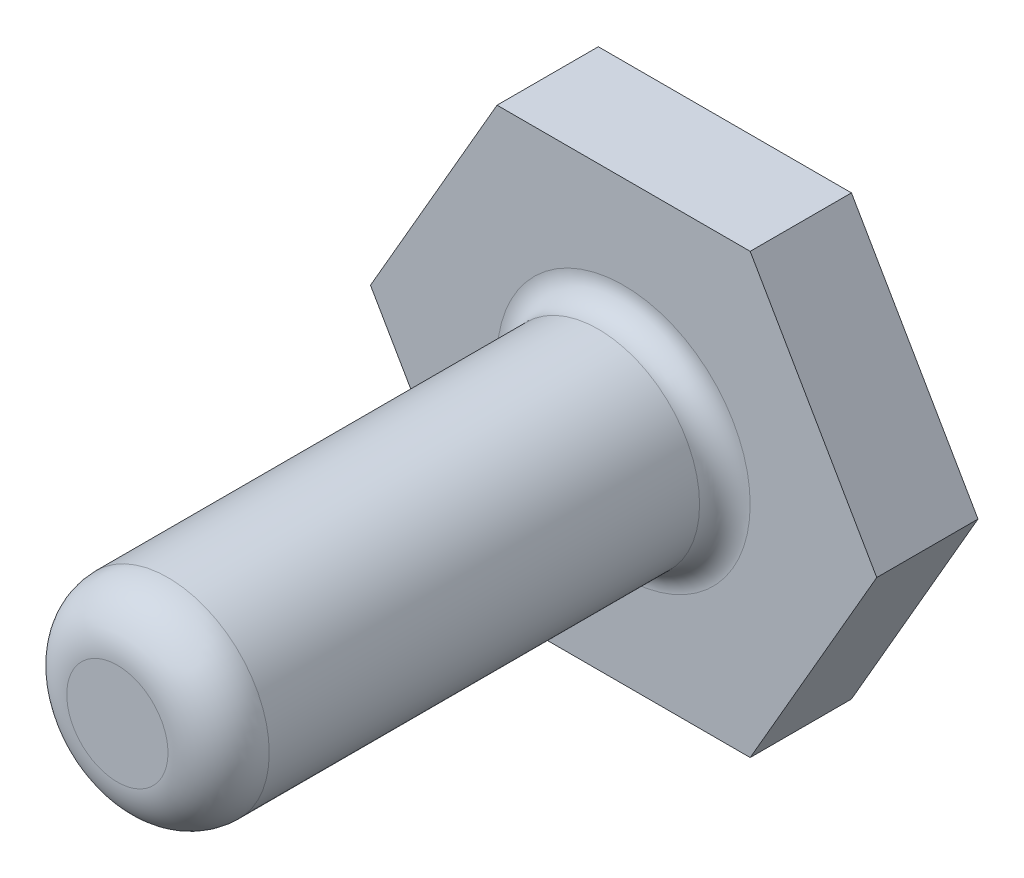
SolidWorks part; units mm, degrees
ref_plane "Front" through (0, 0, 0) normal (0, 0, 1) x (1, 0, 0)
ref_plane "Top" through (0, 0, 0) normal (0, 1, 0) x (1, 0, 0)
ref_plane "Right" through (0, 0, 0) normal (1, 0, 0) x (0, 0, -1)
other "Configuration Table"
sketch "Sketch1" plane through (0, 0, 0) normal (0, 0, 1) x (1, 0, 0)
  line L1 (5, 8.6603) -> (-5, 8.6603)
  line L2 (-5, 8.6603) -> (-10, 0)
  line L3 (-10, 0) -> (-5, -8.6603)
  line L4 (-5, -8.6603) -> (5, -8.6603)
  line L5 (5, -8.6603) -> (10, 0)
  line L6 (10, 0) -> (5, 8.6603)
  circle A0 centre (0, 0) radius 8.6603 construction
  dimension "D1" = 10
extrude "Boss-Extrude1" add sketch "Sketch1" along normal blind 4
sketch "Sketch2" plane through (0, 0, 4) normal (0, 0, 1) x (1, 0, 0)
  circle A0 centre (0, 0) radius 4
  dimension "D1" = 8
extrude "Boss-Extrude2" add sketch "Sketch2" along normal blind 20
fillet "Fillet1" radius 1 1 edges at (4, 0, 4)
fillet "Fillet2" radius 2 1 edges at (4, 0, 24)
